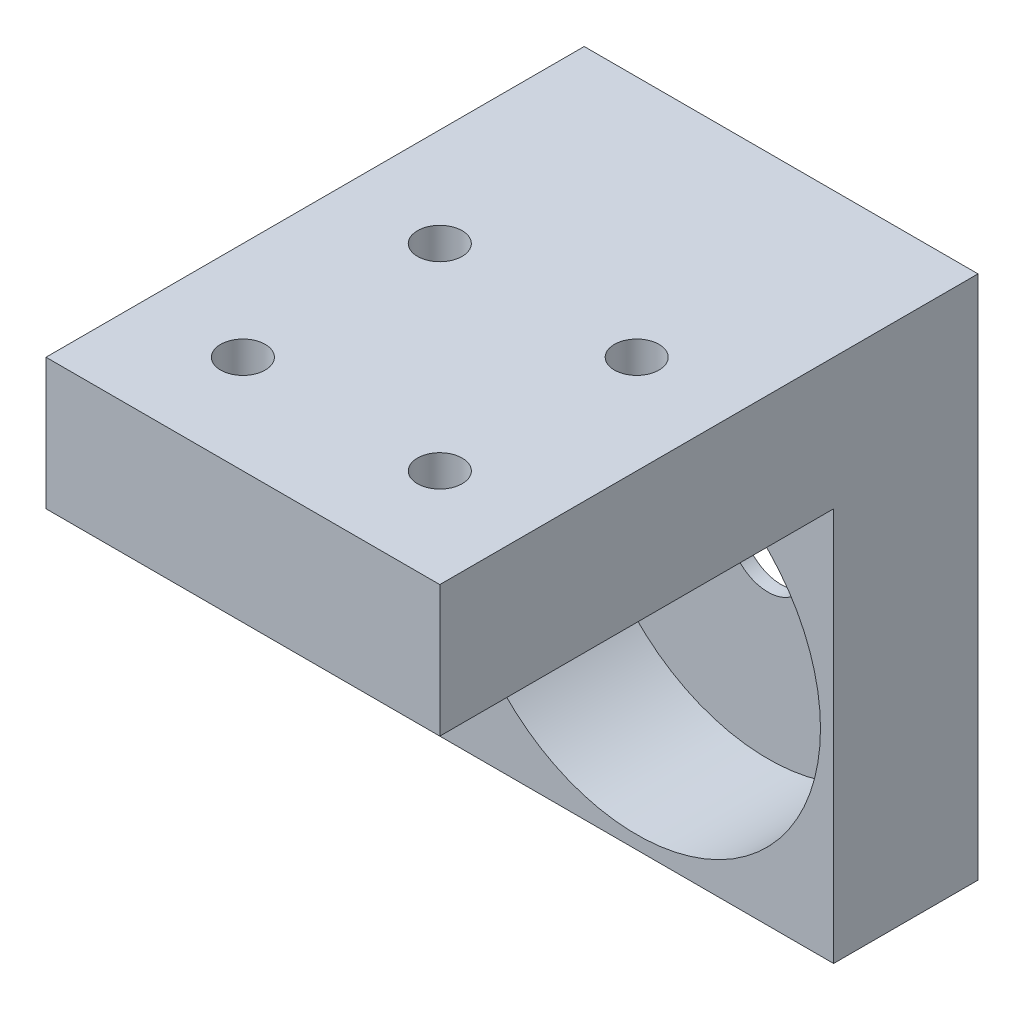
SolidWorks part; units mm, degrees
ref_plane "Front Plane" through (0, 0, 0) normal (0, 0, 1) x (1, 0, 0)
ref_plane "Top Plane" through (0, 0, 0) normal (0, 1, 0) x (1, 0, 0)
ref_plane "Right Plane" through (0, 0, 0) normal (1, 0, 0) x (0, 0, -1)
sketch "Sketch1" plane through (0, 0, 0) normal (0, 0, 1) x (1, 0, 0)
  line L1 (0, 0) -> (30, 0)
  line L2 (0, 0) -> (0, 30)
  line L3 (0, 30) -> (30, 30)
  line L4 (30, 0) -> (30, 30)
  dimension "D1" = 30
  dimension "D2" = 30
extrude "Boss-Extrude1" add sketch "Sketch1" along normal blind 11
sketch "Sketch2" plane through (0, 0, 11) normal (0, 0, 1) x (1, 0, 0)
  line L0 (30, 0) -> (30, 30) construction
  line L1 (30, 30) -> (0, 30) construction
  circle A0 centre (15, 15) radius 14
  dimension "D1" = 28
  dimension "D2" = 15
  dimension "D3" = 15
extrude "Cut-Extrude1" cut sketch "Sketch2" against normal blind 10
sketch "Sketch3" plane through (0, 0, 1) normal (0, 0, 1) x (1, 0, 0)
  line L0 (0, 0) -> (30, 0) construction
  line L1 (0, 30) -> (0, 0) construction
  circle A0 centre (15, 15) radius 3
  dimension "D1" = 6
  dimension "D2" = 15
  dimension "D3" = 15
extrude "Cut-Extrude2" cut sketch "Sketch3" against normal blind 1
sketch "Sketch4" plane through (0, 30, 0) normal (0, 1, 0) x (1, 0, 0)
  line L1 (0, 0) -> (30, 0)
  line L2 (0, 0) -> (0, -41)
  line L3 (0, -41) -> (30, -41)
  line L4 (30, 0) -> (30, -41)
  dimension "D1" = 30
  dimension "D2" = 41
extrude "Boss-Extrude2" add sketch "Sketch4" along normal blind 10
sketch "Sketch5" plane through (0, 30, 0) normal (0, -1, 0) x (1, 0, 0)
  line L0 (30, 11) -> (0, 11) construction
  line L1 (30, 41) -> (30, 11) construction
  line L2 (0, 11) -> (0, 41) construction
  line L3 (0, 11) -> (30, 11) construction
  line L4 (0, 41) -> (30, 41) construction
  circle A0 centre (7.5, 33.5) radius 1.7
  circle A1 centre (22.5, 33.5) radius 1.7
  circle A2 centre (7.5, 18.5) radius 1.7
  circle A3 centre (22.5, 18.5) radius 1.7
  point P14 (0, 0)
  point P16 (-4.6549, 13.7191)
  dimension "D3" = 3.4
  dimension "D4" = 3.4
  dimension "D5" = 3.4
  dimension "D6" = 3.4
  dimension "D1" = 7.5
  dimension "D2" = 7.5
  dimension "D7" = 7.5
  dimension "D8" = 7.5
  dimension "D9" = 7.5
  dimension "D10" = 7.5
  dimension "D11" = 7.5
  dimension "D12" = 7.5
extrude "Cut-Extrude3" cut sketch "Sketch5" against normal through all
